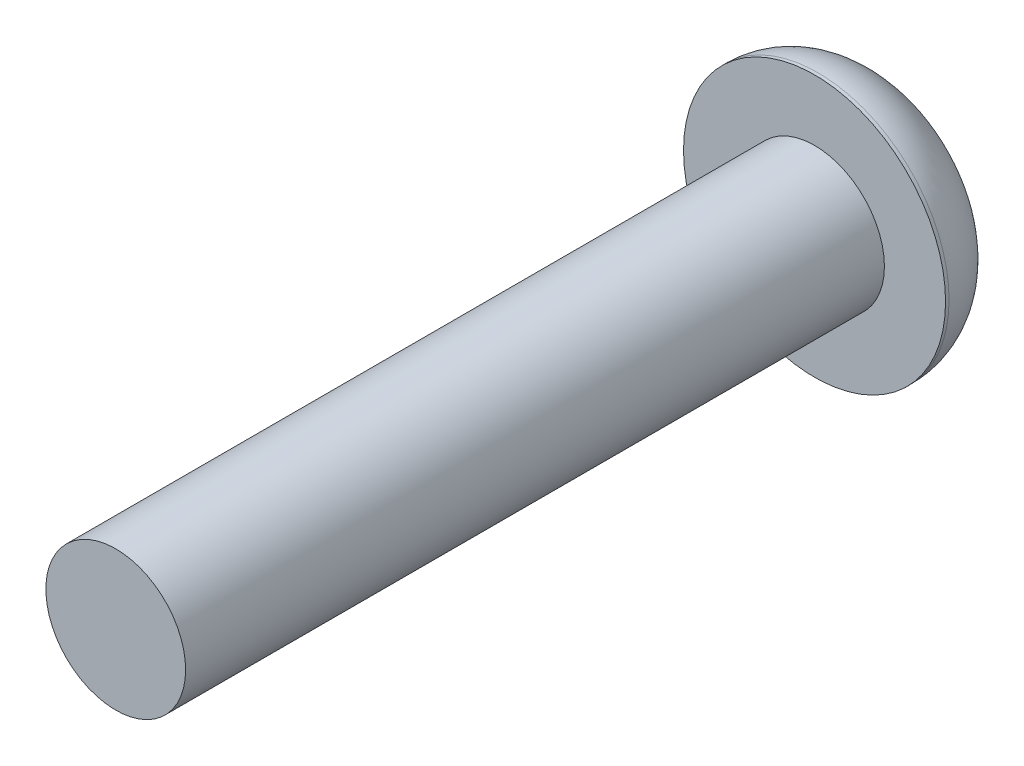
SolidWorks part; units mm, degrees
ref_plane "前视基准面" through (0, 0, 0) normal (0, 0, 1) x (1, 0, 0)
ref_plane "上视基准面" through (0, 0, 0) normal (0, 1, 0) x (1, 0, 0)
ref_plane "右视基准面" through (0, 0, 0) normal (1, 0, 0) x (0, 0, -1)
sketch "草图1" plane through (0, 0, 0) normal (0, 0, 1) x (1, 0, 0)
  circle A0 centre (0, 0) radius 2
extrude "凸台-拉伸1" add sketch "草图1" along normal blind 20
sketch "草图2" plane through (0, 0, 0) normal (0, 0, -1) x (-1, 0, 0)
  circle A0 centre (0, 0) radius 3.75
extrude "凸台-拉伸2" add sketch "草图2" along normal blind 2.1
fillet "圆角1" radius 2 1 edges at (-3.75, 0, -2.1)
